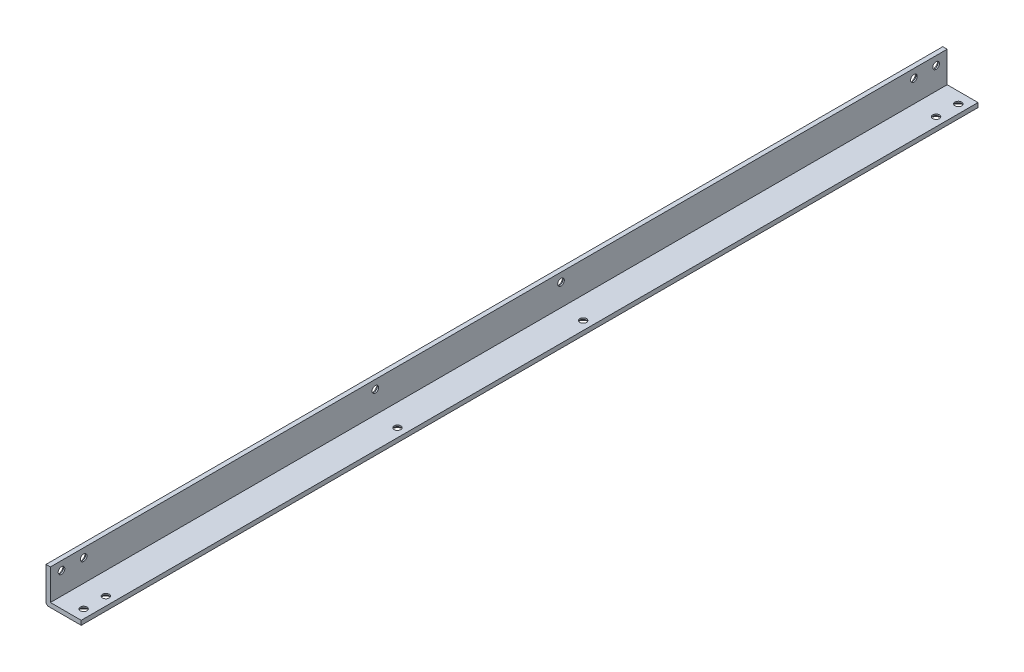
SolidWorks part; units mm, degrees
material "6061 Alloy"
ref_plane "Front Plane" through (0, 0, 0) normal (0, 0, 1) x (1, 0, 0)
ref_plane "Top Plane" through (0, 0, 0) normal (0, 1, 0) x (1, 0, 0)
ref_plane "Right Plane" through (0, 0, 0) normal (1, 0, 0) x (0, 0, -1)
sketch "Sketch1" plane through (0, 0, 0) normal (0, 1, 0) x (1, 0, 0)
  line L1 (0, 0) -> (12.7, 0)
  line L2 (0, 0) -> (0, -323.5)
  line L3 (0, -323.5) -> (12.7, -323.5)
  line L4 (12.7, 0) -> (12.7, -323.5)
  dimension "D1" = 12.7
  dimension "D2" = 323.5
extrude "Boss-Extrude1" add sketch "Sketch1" along normal blind 1.5875
sketch "Sketch2" plane through (0, 1.5875, 0) normal (0, 1, 0) x (1, 0, 0)
  line L0 (0, -323.5) -> (12.7, -323.5) construction
  line L1 (0, 0) -> (1.5875, 0)
  line L2 (0, 0) -> (0, -323.5)
  line L3 (0, -323.5) -> (1.5875, -323.5)
  line L4 (1.5875, 0) -> (1.5875, -323.5)
  dimension "D1" = 1.5875
extrude "Boss-Extrude2" add sketch "Sketch2" along normal blind 11.1125
fillet "Fillet1" radius 1 1 edges at (0, 0, 161.75)
hole_wizard "M2 Clearance Hole1" positions "Sketch3" profile "Sketch4" hole size "M2" standard "ANSI Metric"
sketch "Sketch3" plane through (0, 0, 0) normal (-1, 0, 0) x (0, 0, 1)
  line L0 (0, 12.7) -> (0, 1) construction
  line L1 (323.5, 12.7) -> (323.5, 1) construction
  line L3 (323.5, 1.5875) -> (0, 1.5875) construction
  point P0 (4, 9.5875)
  point P2 (12, 9.5875)
  point P4 (139.3, 9.5875)
  point P6 (206.3, 9.5875)
  point P8 (319.5, 9.5875)
  point P10 (311.5, 9.5875)
  dimension "D1" = 4
  dimension "D2" = 12
  dimension "D3" = 4
  dimension "D4" = 12
  dimension "D5" = 8
  dimension "D6" = 127.3
  dimension "D7" = 67
sketch "Sketch4" plane through (0, 9.5875, 4) normal (0, 1, 0) x (0, 0, 1)
  line L0 (0, 0) -> (0, 2.721)
  line L1 (0, 2.721) -> (1.2, 2)
  line L2 (1.2, 2) -> (1.2, 1.1)
  line L3 (1.2, 1.1) -> (2.3, 0)
  line L5 (2.3, 0) -> (0, 0)
  line L6 (-1.2, 1.1) -> (-2.3, 0) construction
  line L10 (0, 2.721) -> (-1.2, 2) construction
  line L11 (0, -6.35) -> (0, 107.95) construction
  dimension "Hole Dia." = 2.4
  dimension "Hole Depth" = 2
  dimension "Near C'Sink Dia." = 4.6
  dimension "Near C'Sink Angle" = 90
  dimension "Drill Angle" = 118
hole_wizard "M2 Clearance Hole2" positions "Sketch5" profile "Sketch6" hole size "M2" standard "ANSI Metric"
sketch "Sketch5" plane through (0, 0, 0) normal (0, -1, 0) x (-1, 0, 0)
  line L1 (-12.7, 0) -> (-1, 0) construction
  line L2 (-1, -323.5) -> (-12.7, -323.5) construction
  line L3 (-1.5875, -323.5) -> (-1.5875, 0) construction
  point P0 (-9.5875, -4)
  point P2 (-9.5875, -12)
  point P4 (-9.5875, -139.3)
  point P6 (-9.5875, -206.3)
  point P8 (-9.5875, -311.5)
  point P10 (-9.5875, -319.5)
  dimension "D1" = 8
  dimension "D2" = 4
  dimension "D3" = 12
  dimension "D4" = 127.3
  dimension "D5" = 67
  dimension "D6" = 4
  dimension "D7" = 12
sketch "Sketch6" plane through (9.5875, 0, 4) normal (1, 0, 0) x (0, 0, -1)
  line L0 (0, 0) -> (0, 2.721)
  line L1 (0, 2.721) -> (1.2, 2)
  line L2 (1.2, 2) -> (1.2, 1.1)
  line L3 (1.2, 1.1) -> (2.3, 0)
  line L5 (2.3, 0) -> (0, 0)
  line L6 (-1.2, 1.1) -> (-2.3, 0) construction
  line L10 (0, 2.721) -> (-1.2, 2) construction
  line L11 (0, -6.35) -> (0, 107.95) construction
  dimension "Hole Dia." = 2.4
  dimension "Hole Depth" = 2
  dimension "Near C'Sink Dia." = 4.6
  dimension "Near C'Sink Angle" = 90
  dimension "Drill Angle" = 118
